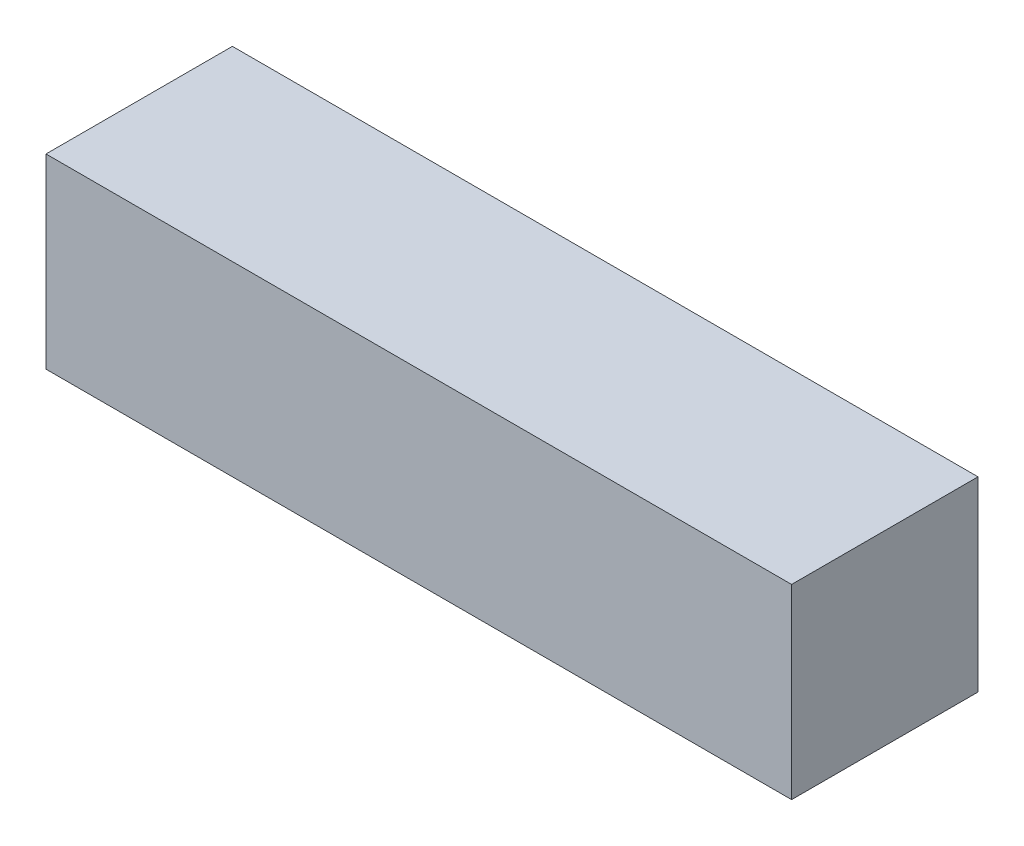
SolidWorks part; units mm, degrees
ref_plane "Ebene vorne" through (0, 0, 0) normal (0, 0, 1) x (1, 0, 0)
ref_plane "Ebene oben" through (0, 0, 0) normal (0, 1, 0) x (1, 0, 0)
ref_plane "Ebene rechts" through (0, 0, 0) normal (1, 0, 0) x (0, 0, -1)
sketch "Sketch1" plane through (0, 0, 0) normal (1, 0, 0) x (0, 0, -1)
  line L0 (-106.9498, 0) -> (127.027, 0) construction
  line L1 (-50, 50) -> (50, 50)
  line L2 (-50, 50) -> (-50, -50)
  line L3 (-50, -50) -> (50, -50)
  line L4 (50, 50) -> (50, -50)
  line L5 (0, 87.8378) -> (0, -79.3436) construction
  dimension "D1" = 100
extrude "Boss-Extrude1" add sketch "Sketch1" along normal blind 400
sketch "Sketch2" plane through (0, 0, 0) normal (-1, 0, 0) x (0, 0, 1)
  circle A0 centre (0, 0) radius 4
  dimension "D1" = 8
extrude "Cut-Extrude1" cut sketch "Sketch2" against normal blind 10
